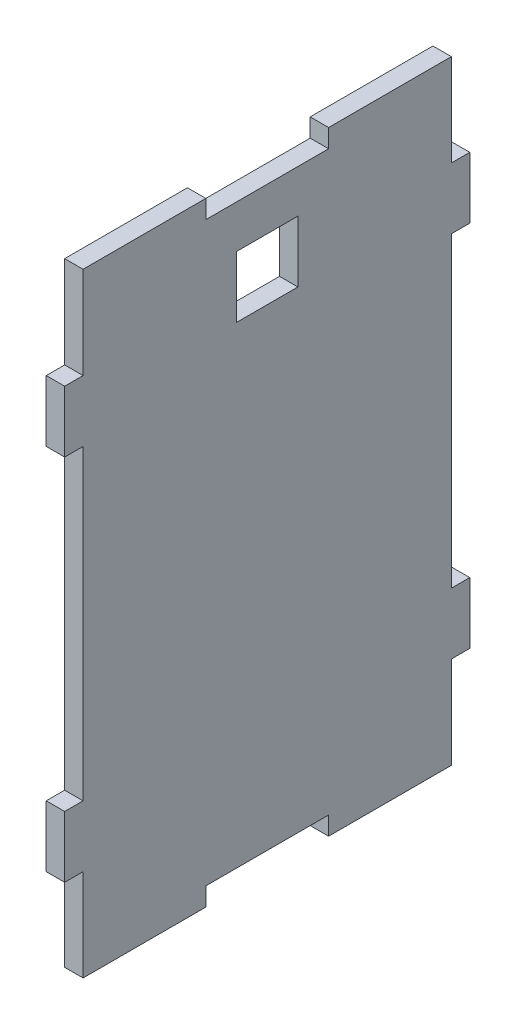
SolidWorks part; units mm, degrees
ref_plane "Front Plane" through (0, 0, 0) normal (0, 0, 1) x (1, 0, 0)
ref_plane "Top Plane" through (0, 0, 0) normal (0, 1, 0) x (1, 0, 0)
ref_plane "Right Plane" through (0, 0, 0) normal (1, 0, 0) x (0, 0, -1)
sketch "Sketch1" plane through (0, 0, 0) normal (1, 0, 0) x (0, 0, -1)
  line L1 (-30, 50) -> (30, 50)
  line L2 (-30, 50) -> (-30, -50)
  line L3 (-30, -50) -> (30, -50)
  line L4 (30, 50) -> (30, -50)
  line L5 (-30, 50) -> (30, -50) construction
  line L6 (-30, -50) -> (30, 50) construction
  point P0 (0, 0)
  dimension "D1" = 60
  dimension "D2" = 100
extrude "Boss-Extrude1" add sketch "Sketch1" along normal blind 3
sketch "Sketch2" plane through (0, 0, 0) normal (1, 0, 0) x (0, 0, -1)
  line L0 (-30, -35) -> (-33, -35)
  line L1 (-30, 50) -> (-30, -50) construction
  line L2 (-33, -35) -> (-33, -25)
  line L3 (-33, -25) -> (-30, -25)
  line L4 (-30, -25) -> (-30, -35)
  line L5 (-30, 25) -> (-33, 25)
  line L6 (-33, 25) -> (-33, 35)
  line L7 (-33, 35) -> (-30, 35)
  line L8 (-30, 35) -> (-30, 25)
  line L9 (30, 35) -> (33, 35)
  line L10 (30, -50) -> (30, 50) construction
  line L11 (33, 35) -> (33, 25)
  line L12 (33, 25) -> (30, 25)
  line L13 (30, 25) -> (30, 35)
  line L14 (30, -35) -> (33, -35)
  line L15 (33, -35) -> (33, -25)
  line L16 (33, -25) -> (30, -25)
  line L17 (30, -25) -> (30, -35)
  line L18 (-33, 30) -> (33, 30) construction
  line L19 (-33, -30) -> (33, -30) construction
  line L20 (-30, -50) -> (30, -50) construction
  line L21 (30, 50) -> (-30, 50) construction
  dimension "D1" = 3
  dimension "D2" = 10
  dimension "D3" = 20
  dimension "D4" = 20
extrude "Boss-Extrude2" add sketch "Sketch2" along normal blind 3
sketch "Sketch3" plane through (3, 0, 0) normal (1, 0, 0) x (0, 0, -1)
  line L0 (-10, 50) -> (-10, 47)
  line L1 (30, 50) -> (-30, 50) construction
  line L2 (-10, 47) -> (10, 47)
  line L3 (10, 47) -> (10, 50)
  line L4 (-10, 50) -> (10, 50)
  line L5 (0, 47) -> (0, 50) construction
  line L6 (-10, -50) -> (-10, -47)
  line L7 (-30, -50) -> (30, -50) construction
  line L8 (-10, -47) -> (10, -47)
  line L9 (10, -47) -> (10, -50)
  line L10 (10, -50) -> (-10, -50)
  line L11 (0, -47) -> (0, -50) construction
  dimension "D1" = 3
  dimension "D2" = 20
  dimension "D3" = 20
  dimension "D4" = 3
extrude "Cut-Extrude1" cut sketch "Sketch3" against normal blind 3
sketch "Sketch4" plane through (3, 0, 0) normal (1, 0, 0) x (0, 0, -1)
  line L0 (0, 47) -> (0, 35) construction
  line L1 (-10, 47) -> (10, 47) construction
  line L3 (-5, 40) -> (5, 40)
  line L4 (-5, 40) -> (-5, 30)
  line L5 (-5, 30) -> (5, 30)
  line L6 (5, 40) -> (5, 30)
  line L7 (-5, 40) -> (5, 30) construction
  line L8 (-5, 30) -> (5, 40) construction
  dimension "D1" = 10
  dimension "D2" = 10
  dimension "D3" = 12
extrude "Cut-Extrude2" cut sketch "Sketch4" against normal blind 3
